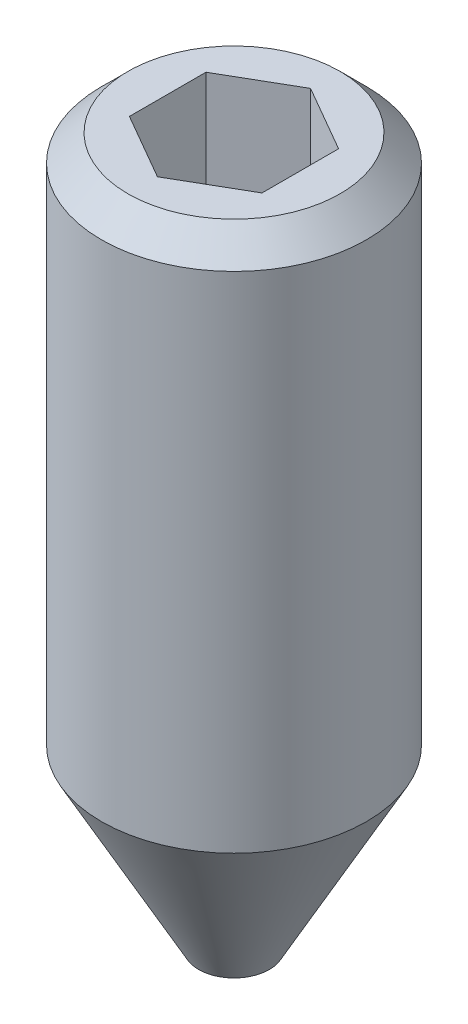
SolidWorks part; units mm, degrees
ref_plane "Plane1" through (0, 0, 0) normal (0, 0, 1) x (1, 0, 0)
ref_plane "Plane2" through (0, 0, 0) normal (0, 1, 0) x (1, 0, 0)
ref_plane "Plane3" through (0, 0, 0) normal (1, 0, 0) x (0, 0, -1)
sketch "Sketch1" plane through (0, 0, 0) normal (0, 0, 1) x (1, 0, 0)
  line L0 (0, -34) -> (0, 29) construction
  line L1 (0, -8) -> (0.4, -8)
  line L2 (0.4, -8) -> (1.5, -6)
  line L3 (1.5, -6) -> (1.5, -0.3)
  line L4 (1.5, -0.3) -> (1.2, 0)
  line L5 (1.2, 0) -> (0, 0)
  line L6 (0, 0) -> (0, -8)
  dimension "D1" = 1.5
  dimension "D2" = 6
  dimension "D3" = 8
  dimension "D4" = 0.4
  dimension "D5" = 0.3
  dimension "D6" = 0.3
revolve "Base-Revolve" add sketch "Sketch1" angle 360 about L0
cosmetic thread "Cosmetic Thread1"
sketch "Sketch2" plane through (0, 0, 0) normal (0, 1, 0) x (1, 0, 0)
  line L0 (0.75, 0.433) -> (0, 0.866)
  line L1 (0, 0.866) -> (-0.75, 0.433)
  line L2 (-0.75, 0.433) -> (-0.75, -0.433)
  line L3 (-0.75, -0.433) -> (0, -0.866)
  line L4 (0, -0.866) -> (0.75, -0.433)
  line L5 (0.75, -0.433) -> (0.75, 0.433)
extrude "Cut-Extrude1" cut sketch "Sketch2" against normal blind 2
